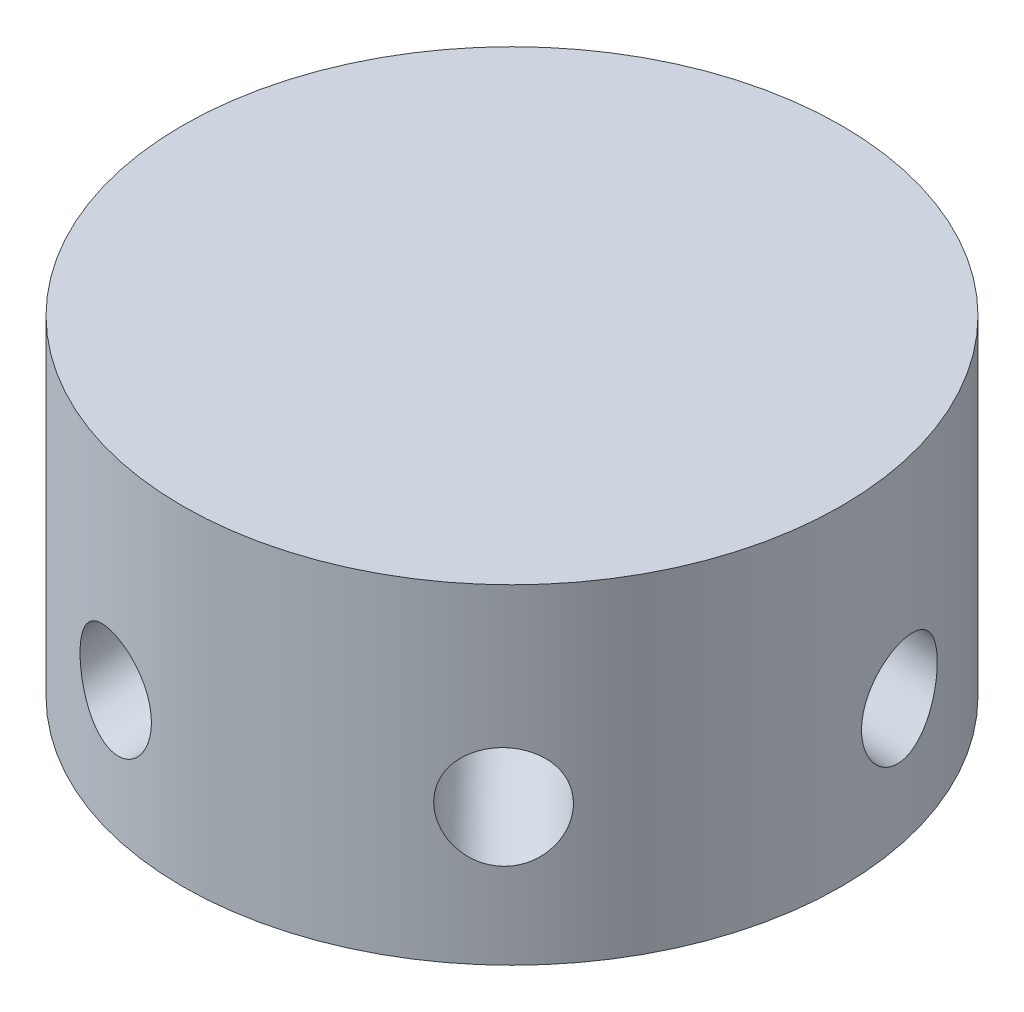
SolidWorks part; units mm, degrees
ref_plane "Front Plane" through (0, 0, 0) normal (0, 0, 1) x (1, 0, 0)
ref_plane "Top Plane" through (0, 0, 0) normal (0, 1, 0) x (1, 0, 0)
ref_plane "Right Plane" through (0, 0, 0) normal (1, 0, 0) x (0, 0, -1)
sketch "Sketch1" plane through (0, 0, 0) normal (0, 1, 0) x (1, 0, 0)
  circle A0 centre (0, 0) radius 10
  dimension "D1" = 20
extrude "base" add sketch "Sketch1" along normal blind 3 and the other way blind 7
ref_axis "6hubaxis" through (0, 5.5, 0) along (0, -1, 0)
ref_plane "Plane1" through (2.6705, -1.0931, 2.7701) normal (-0.6676, 0.2733, -0.6925) x (-0.6559, 0.2243, 0.7208)
sketch "Sketch2" plane through (2.6705, -1.0931, 2.7701) normal (-0.6676, 0.2733, -0.6925) x (-0.6559, 0.2243, 0.7208)
  circle A0 centre (0, 0) radius 1.5 construction
  circle A1 centre (0, 0) radius 1.5
extrude "hole1" cut sketch "Sketch2" against normal through all
pattern_circular "hole1mirror" count 2 over 360 about axis through (0, 5.5, 0) along (0, -1, 0) of "hole1"
ref_plane "Plane2" through (-0.9417, -1.2361, 3.6858) normal (0.2354, 0.309, -0.9215) x (-0.9719, 0.0738, -0.2235)
sketch "Sketch3" plane through (-0.9417, -1.2361, 3.6858) normal (0.2354, 0.309, -0.9215) x (-0.9719, 0.0738, -0.2235)
  circle A0 centre (0, 0) radius 1.5 construction
  circle A1 centre (0, 0) radius 1.5
extrude "hole2" cut sketch "Sketch3" against normal through all
pattern_circular "hole2mirror" count 2 over 360 about axis through (0, 5.5, 0) along (0, -1, 0) of "hole2"
ref_plane "Plane3" through (-3.7178, -1.2361, 0.8061) normal (0.9295, 0.309, -0.2015) x (-0.1912, -0.0636, -0.9795)
sketch "Sketch4" plane through (-3.7178, -1.2361, 0.8061) normal (0.9295, 0.309, -0.2015) x (-0.1912, -0.0636, -0.9795)
  circle A0 centre (0, 0) radius 1.5 construction
  circle A1 centre (0, 0) radius 1.5
extrude "hole3" cut sketch "Sketch4" against normal through all
pattern_circular "hole3mirror" count 2 over 360 about axis through (0, 5.5, 0) along (0, -1, 0) of "hole3"
sketch "Sketch5" plane through (0, -7, 0) normal (0, -1, 0) x (1, 0, 0)
  line L0 (-10, 0) -> (10, 0) construction
  circle A0 centre (0, 0) radius 10 construction
  text T0 "6-1"
extrude "Boss-Extrude1" add sketch "Sketch5" along normal blind 1
